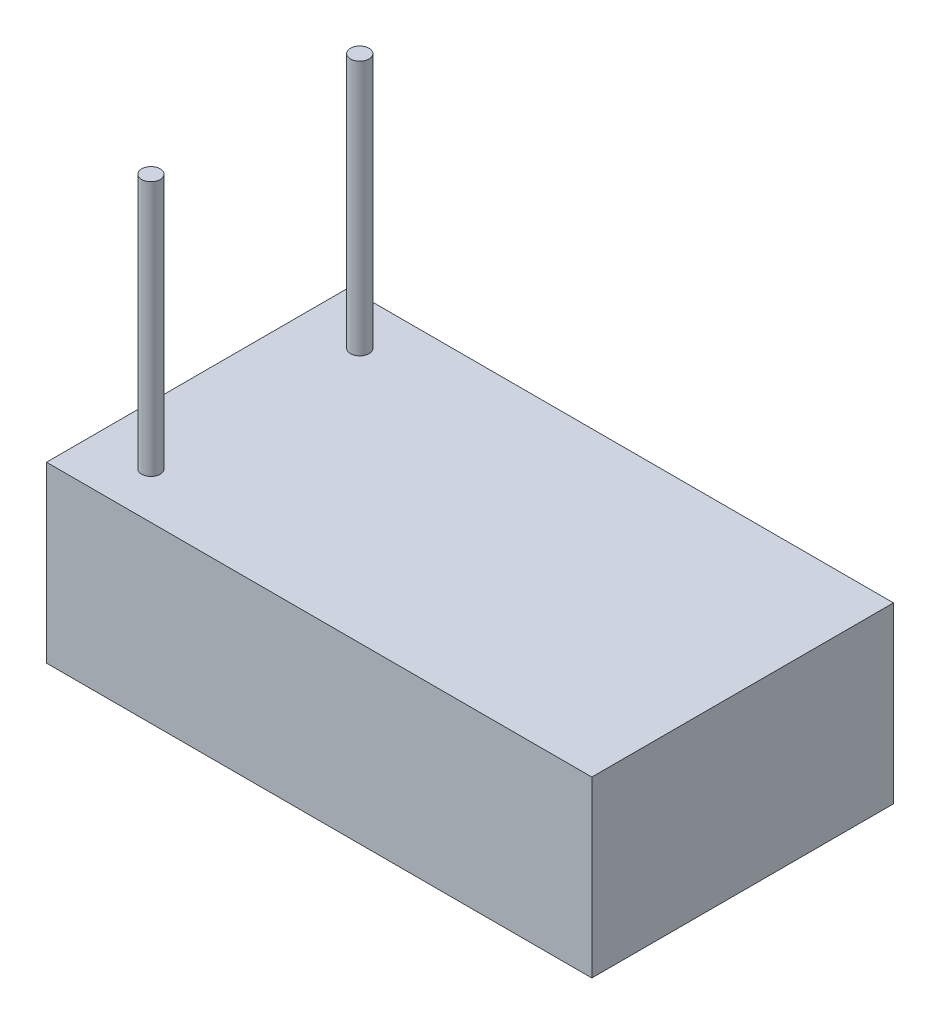
SolidWorks part; units mm, degrees
ref_plane "Front Plane" through (0, 0, 0) normal (0, 0, 1) x (1, 0, 0)
ref_plane "Top Plane" through (0, 0, 0) normal (0, 1, 0) x (1, 0, 0)
ref_plane "Right Plane" through (0, 0, 0) normal (1, 0, 0) x (0, 0, -1)
sketch "SK_P01_Receiver47x26x15" plane through (0, 0, 0) normal (0, 1, 0) x (1, 0, 0)
  line L0 (-23.5, -13) -> (23.5, -13)
  line L1 (23.5, -13) -> (23.5, 13)
  line L2 (23.5, 13) -> (-23.5, 13)
  line L3 (-23.5, 13) -> (-23.5, -13)
extrude "P01_Receiver47x26x15" add sketch "SK_P01_Receiver47x26x15" along normal blind 15
sketch "SK_P02_Antenna" plane through (0, 0, 0) normal (0, 1, 0) x (1, 0, 0)
  circle A0 centre (-18.5, 9) radius 0.8
extrude "P02_Antenna" add sketch "SK_P02_Antenna" along normal blind 22 from offset 15
sketch "SK_P03_Antenna" plane through (0, 0, 0) normal (0, 1, 0) x (1, 0, 0)
  circle A0 centre (-18.5, -9) radius 0.8
extrude "P03_Antenna" add sketch "SK_P03_Antenna" along normal blind 22 from offset 15
